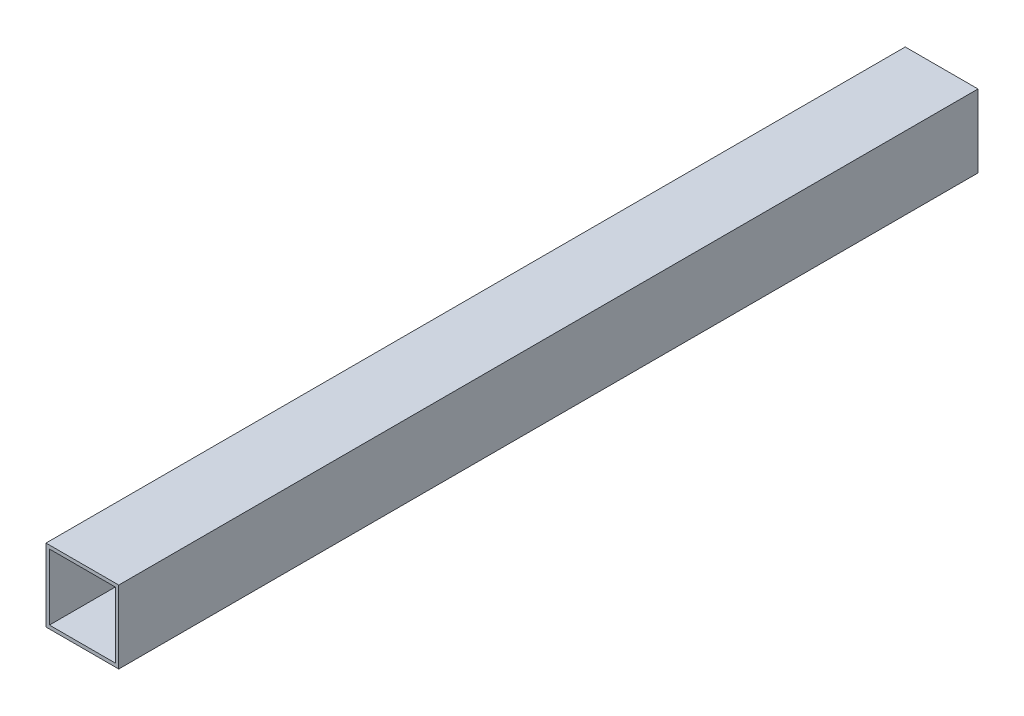
SolidWorks part; units mm, degrees
ref_plane "Front Plane" through (0, 0, 0) normal (0, 0, 1) x (1, 0, 0)
ref_plane "Top Plane" through (0, 0, 0) normal (0, 1, 0) x (1, 0, 0)
ref_plane "Right Plane" through (0, 0, 0) normal (1, 0, 0) x (0, 0, -1)
sketch "Sketch1" plane through (0, 0, 0) normal (0, 0, 1) x (1, 0, 0)
  line L0 (11.5, 11.5) -> (-11.5, 11.5)
  line L1 (12.7, 12.7) -> (-12.7, 12.7)
  line L2 (12.7, 12.7) -> (12.7, -12.7)
  line L3 (12.7, -12.7) -> (-12.7, -12.7)
  line L4 (-12.7, 12.7) -> (-12.7, -12.7)
  line L5 (12.7, 12.7) -> (-12.7, -12.7) construction
  line L6 (12.7, -12.7) -> (-12.7, 12.7) construction
  line L7 (-11.5, 11.5) -> (-11.5, -11.5)
  line L8 (11.5, -11.5) -> (-11.5, -11.5)
  line L9 (11.5, 11.5) -> (11.5, -11.5)
  point P0 (0, 0)
  dimension "D1" = 25.4
  dimension "D2" = 1.2
extrude "Boss-Extrude1" add sketch "Sketch1" along normal mid plane 300
